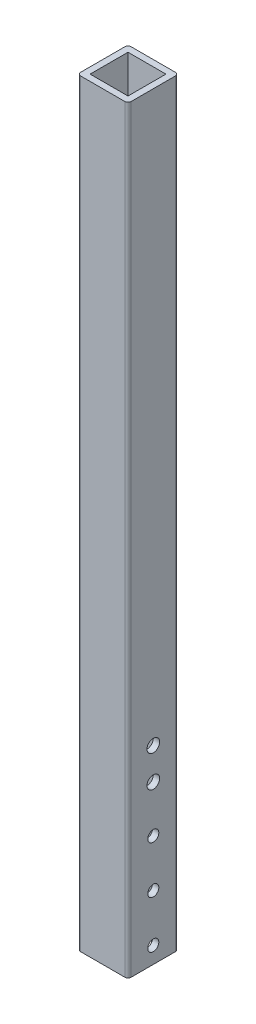
SolidWorks part; units mm, degrees
ref_plane "Front Plane" through (0, 0, 0) normal (0, 0, 1) x (1, 0, 0)
ref_plane "Top Plane" through (0, 0, 0) normal (0, 1, 0) x (1, 0, 0)
ref_plane "Right Plane" through (0, 0, 0) normal (1, 0, 0) x (0, 0, -1)
sketch "Sketch1" plane through (0, 0, 0) normal (0, 1, 0) x (1, 0, 0)
  line L0 (-3.7544, 4.3158) -> (-3.7544, -7.6842)
  line L1 (-5.7544, 6.3158) -> (10.2456, 6.3158)
  line L2 (-5.7544, 6.3158) -> (-5.7544, -9.6842)
  line L3 (-5.7544, -9.6842) -> (10.2456, -9.6842)
  line L4 (10.2456, 6.3158) -> (10.2456, -9.6842)
  line L5 (-3.7544, -7.6842) -> (8.2456, -7.6842)
  line L6 (8.2456, 4.3158) -> (8.2456, -7.6842)
  line L7 (-3.7544, 4.3158) -> (8.2456, 4.3158)
  dimension "D1" = 16
  dimension "D2" = 16
  dimension "D3" = 2
extrude "Boss-Extrude1" add sketch "Sketch1" along normal blind 240
fillet "Fillet1" radius 1 4 edges at (-5.7544, 120, 9.6842) (-5.7544, 120, -6.3158) (10.2456, 120, 9.6842) (10.2456, 120, -6.3158)
sketch "Sketch2" plane through (10.2456, 0, 0) normal (1, 0, 0) x (0, 0, -1)
  line L0 (-9.6842, 0) -> (-9.6842, 240) construction
  line L2 (-8.6842, 0) -> (5.3158, 0) construction
  circle A0 centre (-1.6842, 35.25) radius 1.75
  circle A1 centre (-1.6842, 5.25) radius 1.75
  circle A2 centre (-1.6842, 20.25) radius 1.75
  dimension "D2" = 3.5
  dimension "D3" = 3.5
  dimension "D4" = 3.5
  dimension "D1" = 30
  dimension "D5" = 8
  dimension "D6" = 15
  dimension "D7" = 5.25
extrude "Cut-Extrude1" cut sketch "Sketch2" against normal blind 20
sketch "Sketch3" plane through (10.2456, 0, 0) normal (1, 0, 0) x (0, 0, -1)
  line L0 (-8.6842, 0) -> (5.3158, 0) construction
  line L2 (-9.6842, 0) -> (-9.6842, 240) construction
  circle A0 centre (-1.6842, 60) radius 2
  circle A1 centre (-1.6842, 50) radius 2
  point P8 (5.3158, 91.9171)
  dimension "D5" = 4
  dimension "D6" = 4
  dimension "D1" = 50
  dimension "D2" = 10
  dimension "D3" = 8
  dimension "D4" = 8
extrude "Cut-Extrude2" cut sketch "Sketch3" against normal blind 20
